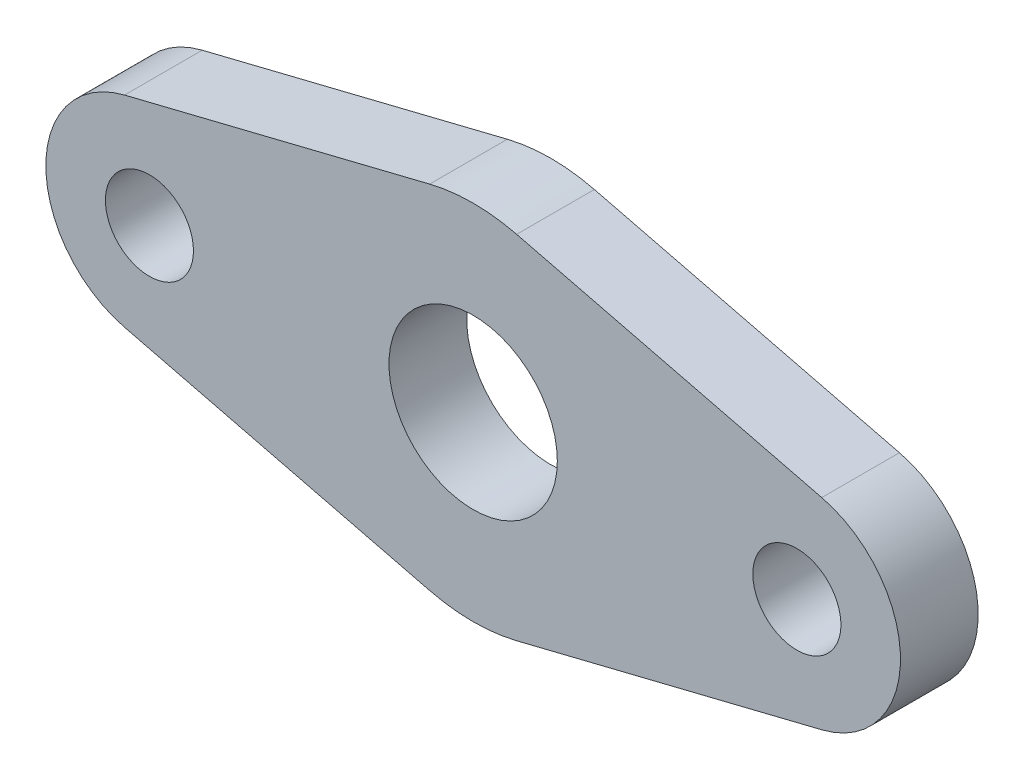
SolidWorks part; units mm, degrees
material "Thornel Mat VMA"
ref_plane "前视基准面" through (0, 0, 0) normal (0, 0, 1) x (1, 0, 0)
ref_plane "上视基准面" through (0, 0, 0) normal (0, 1, 0) x (1, 0, 0)
ref_plane "右视基准面" through (0, 0, 0) normal (1, 0, 0) x (0, 0, -1)
sketch "草图1" plane through (0, 0, 0) normal (0, 0, 1) x (1, 0, 0)
  line L0 (12.5, 0) -> (-12.5, 0) construction
  line L1 (-13.46, 3.8831) -> (-1.68, 6.7954)
  line L2 (55, 0) -> (-55, 0) construction
  line L3 (-13.46, -3.8831) -> (-1.68, -6.7954)
  line L4 (0, -55) -> (0, 55) construction
  line L5 (13.46, 3.8831) -> (1.68, 6.7954)
  line L6 (13.46, -3.8831) -> (1.68, -6.7954)
  circle A0 centre (-12.5, 0) radius 1.7
  circle A2 centre (0, 0) radius 3.25
  arc A3 (-13.46, 3.8831) -> (-13.46, -3.8831) centre (-12.5, 0) ccw
  arc A4 (1.68, 6.7954) -> (-1.68, 6.7954) centre (0, 0) ccw
  arc A5 (1.68, -6.7954) -> (-1.68, -6.7954) centre (0, 0) cw
  arc A6 (13.46, 3.8831) -> (13.46, -3.8831) centre (12.5, 0) cw
  circle A7 centre (12.5, 0) radius 1.7
  point P11 (3.6413, 8.9829)
  point P12 (-13.3642, -4.1824)
  point P18 (-14.1779, -3.9959)
  point P24 (0, 0)
  dimension "D2" = 3.4
  dimension "D3" = 6.5
  dimension "D4" = 4
  dimension "D5" = 7
  dimension "D1" = 25
extrude "凸台-拉伸1" add sketch "草图1" along normal blind 3
